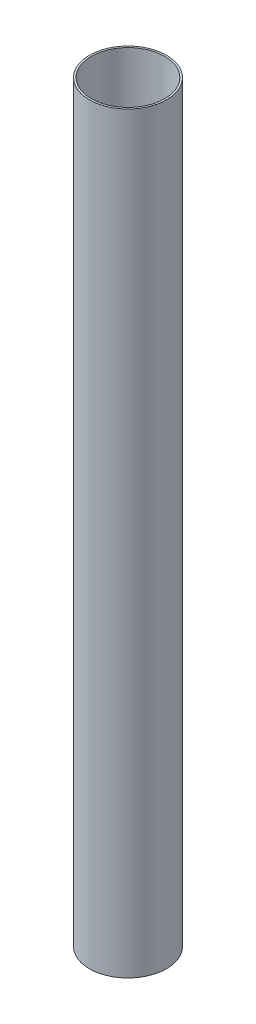
SolidWorks part; units mm, degrees
material "6063-T6"
ref_plane "Front Plane" through (0, 0, 0) normal (0, 0, 1) x (1, 0, 0)
ref_plane "Top Plane" through (0, 0, 0) normal (0, 1, 0) x (1, 0, 0)
ref_plane "Right Plane" through (0, 0, 0) normal (1, 0, 0) x (0, 0, -1)
sketch "Sketch1" plane through (0, 0, 0) normal (0, 1, 0) x (1, 0, 0)
  circle A0 centre (0, 0) radius 24.1554
  circle A1 centre (0, 0) radius 25.4
  dimension "D1" = 50.8
  dimension "D2" = 1.2446
extrude "body" add sketch "Sketch1" along normal blind 495.3
